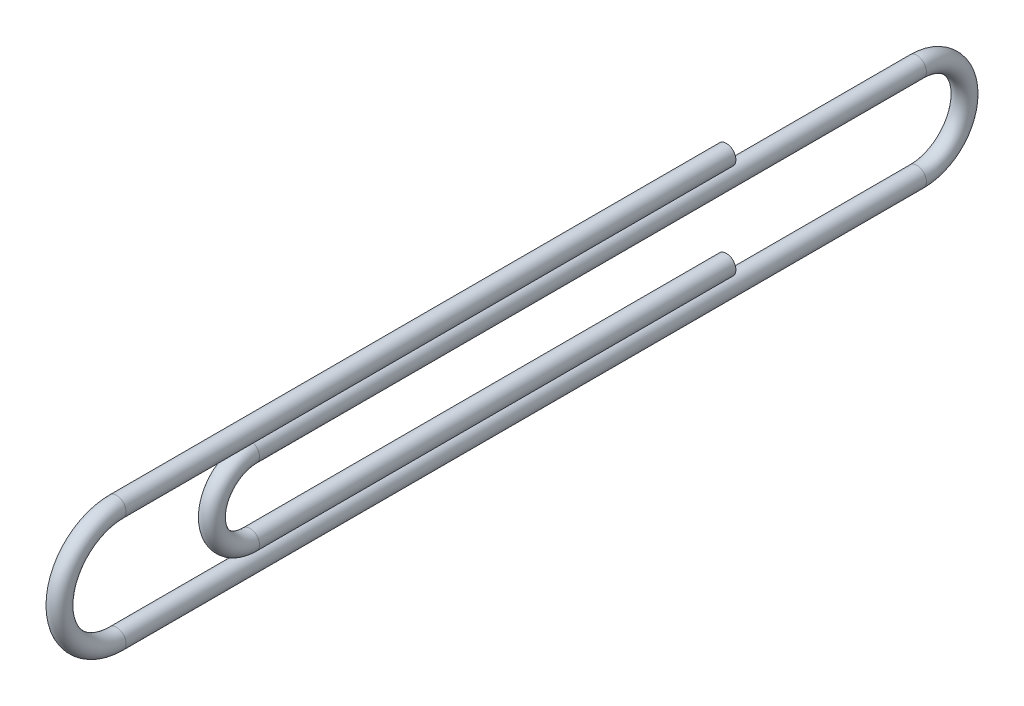
SolidWorks part; units mm, degrees
ref_plane "Front Plane" through (0, 0, 0) normal (1, 0, 0) x (0, 1, 0)
ref_plane "Top Plane" through (0, 0, 0) normal (0, 0, 1) x (0, 1, 0)
ref_plane "Right Plane" through (0, 0, 0) normal (0, 1, 0) x (-1, 0, 0)
sketch "Sketch1" plane through (0, 0, 0) normal (1, 0, 0) x (0, 1, 0)
  line L0 (0, 0) -> (0, 32)
  line L1 (-6, 32) -> (-6, -10)
  line L2 (-1, -10) -> (-1, 25)
  line L3 (-5, 25) -> (-5, 0)
  arc A0 (0, 32) -> (-6, 32) centre (-3, 32) ccw
  arc A1 (-6, -10) -> (-1, -10) centre (-3.5, -10) ccw
  arc A2 (-1, 25) -> (-5, 25) centre (-3, 25) ccw
  point P11 (0, 0)
  point P13 (0, 0)
  point P14 (0, 0)
  dimension "D2" = 3
  dimension "D3" = 2
  dimension "D1" = 42
  dimension "D4" = 32
  dimension "D5" = 35
  dimension "D6" = 25
sweep "Sweep12" add path "Sketch1" circular profile diameter 0.9999 parameters "D3"=0.9999
